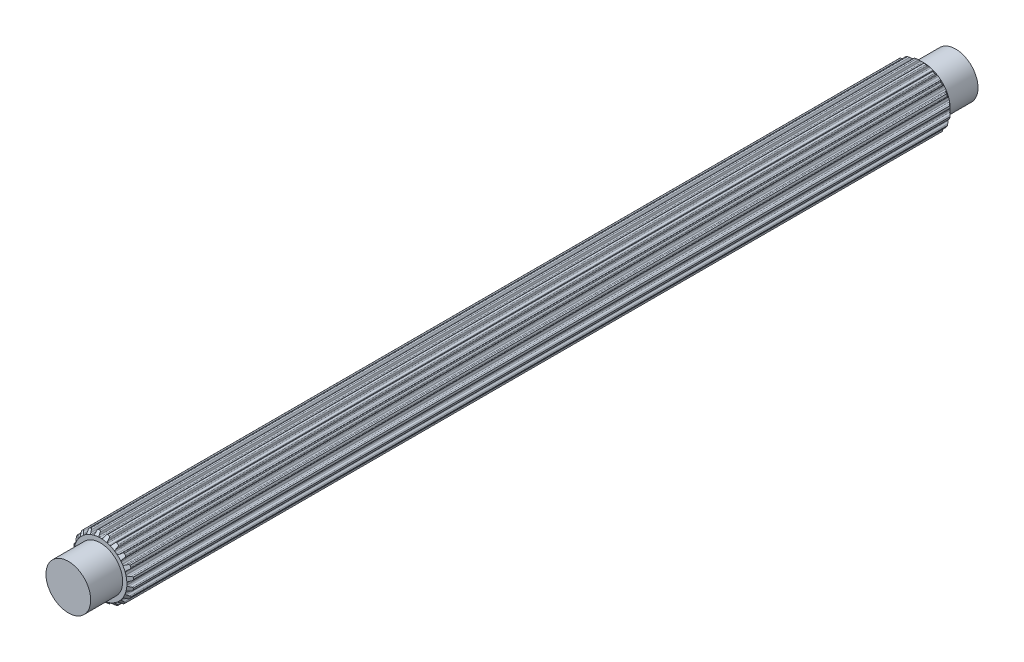
SolidWorks part; units mm, degrees
ref_plane "Front Plane" through (0, 0, 0) normal (0, 0, 1) x (1, 0, 0)
ref_plane "Top Plane" through (0, 0, 0) normal (0, 1, 0) x (1, 0, 0)
ref_plane "Right Plane" through (0, 0, 0) normal (1, 0, 0) x (0, 0, -1)
sketch "Sketch1" plane through (0, 0, 0) normal (0, 0, 1) x (1, 0, 0)
  line L0 (-0.1069, 2.9699) -> (0.1069, 2.9699)
  line L1 (0.3159, 3.2375) -> (0.2537, 3.0575)
  line L2 (-0.2964, 3.2367) -> (-0.2318, 3.0575)
  line L3 (-0.2964, 3.2367) -> (0.3159, 3.2375) construction
  line L4 (0, 3.3252) -> (0, 0) construction
  line L5 (-0.2318, 3.0575) -> (0.2537, 3.0575) construction
  line L6 (-0.4281, 3.3241) -> (0.4281, 3.3263) construction
  line L7 (0.7183, 3.1698) -> (0.7244, 2.9795)
  line L8 (0.816, 2.8576) -> (1.0195, 2.7915)
  line L9 (1.3009, 2.9815) -> (1.1862, 2.8295)
  line L10 (1.6627, 2.7927) -> (1.6097, 2.6099)
  line L11 (1.6591, 2.4655) -> (1.8322, 2.3398)
  line L12 (2.1585, 2.4335) -> (2.0025, 2.3245)
  line L13 (2.4443, 2.1423) -> (2.3374, 1.9847)
  line L14 (2.3398, 1.8322) -> (2.4655, 1.6591)
  line L15 (2.8049, 1.6474) -> (2.6228, 1.5919)
  line L16 (2.9866, 1.2821) -> (2.8363, 1.1653)
  line L17 (2.7915, 1.0195) -> (2.8576, 0.816)
  line L18 (3.1767, 0.7) -> (2.9863, 0.7035)
  line L19 (3.2367, 0.2964) -> (3.0575, 0.2318)
  line L20 (2.9699, 0.1069) -> (2.9699, -0.1069)
  line L21 (3.2375, -0.3159) -> (3.0575, -0.2537)
  line L22 (3.1698, -0.7183) -> (2.9795, -0.7244)
  line L23 (2.8576, -0.816) -> (2.7915, -1.0195)
  line L24 (2.9815, -1.3009) -> (2.8295, -1.1862)
  line L25 (2.7927, -1.6627) -> (2.6099, -1.6097)
  line L26 (2.4655, -1.6591) -> (2.3398, -1.8322)
  line L27 (2.4335, -2.1585) -> (2.3245, -2.0025)
  line L28 (2.1423, -2.4443) -> (1.9847, -2.3374)
  line L29 (1.8322, -2.3398) -> (1.6591, -2.4655)
  line L30 (1.6474, -2.8049) -> (1.5919, -2.6228)
  line L31 (1.2821, -2.9866) -> (1.1653, -2.8363)
  line L32 (1.0195, -2.7915) -> (0.816, -2.8576)
  line L33 (0.7, -3.1767) -> (0.7035, -2.9863)
  line L34 (0.2964, -3.2367) -> (0.2318, -3.0575)
  line L35 (0.1069, -2.9699) -> (-0.1069, -2.9699)
  line L36 (-0.3159, -3.2375) -> (-0.2537, -3.0575)
  line L37 (-0.7183, -3.1698) -> (-0.7244, -2.9795)
  line L38 (-0.816, -2.8576) -> (-1.0195, -2.7915)
  line L39 (-1.3009, -2.9815) -> (-1.1862, -2.8295)
  line L40 (-1.6627, -2.7927) -> (-1.6097, -2.6099)
  line L41 (-1.6591, -2.4655) -> (-1.8322, -2.3398)
  line L42 (-2.1585, -2.4335) -> (-2.0025, -2.3245)
  line L43 (-2.4443, -2.1423) -> (-2.3374, -1.9847)
  line L44 (-2.3398, -1.8322) -> (-2.4655, -1.6591)
  line L45 (-2.8049, -1.6474) -> (-2.6228, -1.5919)
  line L46 (-2.9866, -1.2821) -> (-2.8363, -1.1653)
  line L47 (-2.7915, -1.0195) -> (-2.8576, -0.816)
  line L48 (-3.1767, -0.7) -> (-2.9863, -0.7035)
  line L49 (-3.2367, -0.2964) -> (-3.0575, -0.2318)
  line L50 (-2.9699, -0.1069) -> (-2.9699, 0.1069)
  line L51 (-3.2375, 0.3159) -> (-3.0575, 0.2537)
  line L52 (-3.1698, 0.7183) -> (-2.9795, 0.7244)
  line L53 (-2.8576, 0.816) -> (-2.7915, 1.0195)
  line L54 (-2.9815, 1.3009) -> (-2.8295, 1.1862)
  line L55 (-2.7927, 1.6627) -> (-2.6099, 1.6097)
  line L56 (-2.4655, 1.6591) -> (-2.3398, 1.8322)
  line L57 (-2.4335, 2.1585) -> (-2.3245, 2.0025)
  line L58 (-2.1423, 2.4443) -> (-1.9847, 2.3374)
  line L59 (-1.8322, 2.3398) -> (-1.6591, 2.4655)
  line L60 (-1.6474, 2.8049) -> (-1.5919, 2.6228)
  line L61 (-1.2821, 2.9866) -> (-1.1653, 2.8363)
  line L62 (-1.0195, 2.7915) -> (-0.816, 2.8576)
  line L63 (-0.7, 3.1767) -> (-0.7035, 2.9863)
  line L64 (0.4281, 3.3263) -> (0.62, 3.2938)
  line L65 (1.4351, 3.0312) -> (1.6075, 2.9409)
  line L66 (2.3015, 2.4394) -> (2.4376, 2.3003)
  line L67 (2.9427, 1.6088) -> (3.0291, 1.4344)
  line L68 (3.2958, 0.6207) -> (3.3241, 0.4281)
  line L69 (3.3263, -0.4281) -> (3.2938, -0.62)
  line L70 (3.0312, -1.4351) -> (2.9409, -1.6075)
  line L71 (2.4394, -2.3015) -> (2.3003, -2.4376)
  line L72 (1.6088, -2.9427) -> (1.4344, -3.0291)
  line L73 (0.6207, -3.2958) -> (0.4281, -3.3241)
  line L74 (-0.4281, -3.3263) -> (-0.62, -3.2938)
  line L75 (-1.4351, -3.0312) -> (-1.6075, -2.9409)
  line L76 (-2.3015, -2.4394) -> (-2.4376, -2.3003)
  line L77 (-2.9427, -1.6088) -> (-3.0291, -1.4344)
  line L78 (-3.2958, -0.6207) -> (-3.3241, -0.4281)
  line L79 (-3.3263, 0.4281) -> (-3.2938, 0.62)
  line L80 (-3.0312, 1.4351) -> (-2.9409, 1.6075)
  line L81 (-2.4394, 2.3015) -> (-2.3003, 2.4376)
  line L82 (-1.6088, 2.9427) -> (-1.4344, 3.0291)
  line L83 (-0.6207, 3.2958) -> (-0.4281, 3.3241)
  arc A0 (0.2537, 3.0575) -> (0.1069, 2.9699) centre (0.1283, 3.1009) cw
  arc A1 (-0.2318, 3.0575) -> (-0.1069, 2.9699) centre (-0.1069, 3.1026) ccw
  arc A2 (0.62, 3.2938) -> (0.7183, 3.1698) centre (0.5856, 3.1656) cw
  arc A3 (0.7244, 2.9795) -> (0.816, 2.8576) centre (0.857, 2.9838) ccw
  arc A4 (-0.4281, 3.3241) -> (-0.2964, 3.2367) centre (-0.4213, 3.1916) cw
  arc A5 (0.4281, 3.3263) -> (0.3159, 3.2375) centre (0.4413, 3.1942) ccw
  arc A6 (1.1862, 2.8295) -> (1.0195, 2.7915) centre (1.0802, 2.9095) cw
  arc A7 (1.4351, 3.0312) -> (1.3009, 2.9815) centre (1.4068, 2.9015) ccw
  arc A8 (1.6075, 2.9409) -> (1.6627, 2.7927) centre (1.5352, 2.8297) cw
  arc A9 (1.6097, 2.6099) -> (1.6591, 2.4655) centre (1.7371, 2.5729) ccw
  arc A10 (2.0025, 2.3245) -> (1.8322, 2.3398) centre (1.9264, 2.4332) cw
  arc A11 (2.3015, 2.4394) -> (2.1585, 2.4335) centre (2.2346, 2.3248) ccw
  arc A12 (2.4376, 2.3003) -> (2.4443, 2.1423) centre (2.3345, 2.2168) cw
  arc A13 (2.3374, 1.9847) -> (2.3398, 1.8322) centre (2.4472, 1.9102) ccw
  arc A14 (2.6228, 1.5919) -> (2.4655, 1.6591) centre (2.5841, 1.7189) cw
  arc A15 (2.9427, 1.6088) -> (2.8049, 1.6474) centre (2.8436, 1.5205) ccw
  arc A16 (3.0291, 1.4344) -> (2.9866, 1.2821) centre (2.9052, 1.3869) cw
  arc A17 (2.8363, 1.1653) -> (2.7915, 1.0195) centre (2.9177, 1.0605) ccw
  arc A18 (2.9863, 0.7035) -> (2.8576, 0.816) centre (2.9887, 0.8362) cw
  arc A19 (3.2958, 0.6207) -> (3.1767, 0.7) centre (3.1743, 0.5673) ccw
  arc A20 (3.3241, 0.4281) -> (3.2367, 0.2964) centre (3.1916, 0.4213) cw
  arc A21 (3.0575, 0.2318) -> (2.9699, 0.1069) centre (3.1026, 0.1069) ccw
  arc A22 (3.0575, -0.2537) -> (2.9699, -0.1069) centre (3.1009, -0.1283) cw
  arc A23 (3.3263, -0.4281) -> (3.2375, -0.3159) centre (3.1942, -0.4413) ccw
  arc A24 (3.2938, -0.62) -> (3.1698, -0.7183) centre (3.1656, -0.5856) cw
  arc A25 (2.9795, -0.7244) -> (2.8576, -0.816) centre (2.9838, -0.857) ccw
  arc A26 (2.8295, -1.1862) -> (2.7915, -1.0195) centre (2.9095, -1.0802) cw
  arc A27 (3.0312, -1.4351) -> (2.9815, -1.3009) centre (2.9015, -1.4068) ccw
  arc A28 (2.9409, -1.6075) -> (2.7927, -1.6627) centre (2.8297, -1.5352) cw
  arc A29 (2.6099, -1.6097) -> (2.4655, -1.6591) centre (2.5729, -1.7371) ccw
  arc A30 (2.3245, -2.0025) -> (2.3398, -1.8322) centre (2.4332, -1.9264) cw
  arc A31 (2.4394, -2.3015) -> (2.4335, -2.1585) centre (2.3248, -2.2346) ccw
  arc A32 (2.3003, -2.4376) -> (2.1423, -2.4443) centre (2.2168, -2.3345) cw
  arc A33 (1.9847, -2.3374) -> (1.8322, -2.3398) centre (1.9102, -2.4472) ccw
  arc A34 (1.5919, -2.6228) -> (1.6591, -2.4655) centre (1.7189, -2.5841) cw
  arc A35 (1.6088, -2.9427) -> (1.6474, -2.8049) centre (1.5205, -2.8436) ccw
  arc A36 (1.4344, -3.0291) -> (1.2821, -2.9866) centre (1.3869, -2.9052) cw
  arc A37 (1.1653, -2.8363) -> (1.0195, -2.7915) centre (1.0605, -2.9177) ccw
  arc A38 (0.7035, -2.9863) -> (0.816, -2.8576) centre (0.8362, -2.9887) cw
  arc A39 (0.6207, -3.2958) -> (0.7, -3.1767) centre (0.5673, -3.1743) ccw
  arc A40 (0.4281, -3.3241) -> (0.2964, -3.2367) centre (0.4213, -3.1916) cw
  arc A41 (0.2318, -3.0575) -> (0.1069, -2.9699) centre (0.1069, -3.1026) ccw
  arc A42 (-0.2537, -3.0575) -> (-0.1069, -2.9699) centre (-0.1283, -3.1009) cw
  arc A43 (-0.4281, -3.3263) -> (-0.3159, -3.2375) centre (-0.4413, -3.1942) ccw
  arc A44 (-0.62, -3.2938) -> (-0.7183, -3.1698) centre (-0.5856, -3.1656) cw
  arc A45 (-0.7244, -2.9795) -> (-0.816, -2.8576) centre (-0.857, -2.9838) ccw
  arc A46 (-1.1862, -2.8295) -> (-1.0195, -2.7915) centre (-1.0802, -2.9095) cw
  arc A47 (-1.4351, -3.0312) -> (-1.3009, -2.9815) centre (-1.4068, -2.9015) ccw
  arc A48 (-1.6075, -2.9409) -> (-1.6627, -2.7927) centre (-1.5352, -2.8297) cw
  arc A49 (-1.6097, -2.6099) -> (-1.6591, -2.4655) centre (-1.7371, -2.5729) ccw
  arc A50 (-2.0025, -2.3245) -> (-1.8322, -2.3398) centre (-1.9264, -2.4332) cw
  arc A51 (-2.3015, -2.4394) -> (-2.1585, -2.4335) centre (-2.2346, -2.3248) ccw
  arc A52 (-2.4376, -2.3003) -> (-2.4443, -2.1423) centre (-2.3345, -2.2168) cw
  arc A53 (-2.3374, -1.9847) -> (-2.3398, -1.8322) centre (-2.4472, -1.9102) ccw
  arc A54 (-2.6228, -1.5919) -> (-2.4655, -1.6591) centre (-2.5841, -1.7189) cw
  arc A55 (-2.9427, -1.6088) -> (-2.8049, -1.6474) centre (-2.8436, -1.5205) ccw
  arc A56 (-3.0291, -1.4344) -> (-2.9866, -1.2821) centre (-2.9052, -1.3869) cw
  arc A57 (-2.8363, -1.1653) -> (-2.7915, -1.0195) centre (-2.9177, -1.0605) ccw
  arc A58 (-2.9863, -0.7035) -> (-2.8576, -0.816) centre (-2.9887, -0.8362) cw
  arc A59 (-3.2958, -0.6207) -> (-3.1767, -0.7) centre (-3.1743, -0.5673) ccw
  arc A60 (-3.3241, -0.4281) -> (-3.2367, -0.2964) centre (-3.1916, -0.4213) cw
  arc A61 (-3.0575, -0.2318) -> (-2.9699, -0.1069) centre (-3.1026, -0.1069) ccw
  arc A62 (-3.0575, 0.2537) -> (-2.9699, 0.1069) centre (-3.1009, 0.1283) cw
  arc A63 (-3.3263, 0.4281) -> (-3.2375, 0.3159) centre (-3.1942, 0.4413) ccw
  arc A64 (-3.2938, 0.62) -> (-3.1698, 0.7183) centre (-3.1656, 0.5856) cw
  arc A65 (-2.9795, 0.7244) -> (-2.8576, 0.816) centre (-2.9838, 0.857) ccw
  arc A66 (-2.8295, 1.1862) -> (-2.7915, 1.0195) centre (-2.9095, 1.0802) cw
  arc A67 (-3.0312, 1.4351) -> (-2.9815, 1.3009) centre (-2.9015, 1.4068) ccw
  arc A68 (-2.9409, 1.6075) -> (-2.7927, 1.6627) centre (-2.8297, 1.5352) cw
  arc A69 (-2.6099, 1.6097) -> (-2.4655, 1.6591) centre (-2.5729, 1.7371) ccw
  arc A70 (-2.3245, 2.0025) -> (-2.3398, 1.8322) centre (-2.4332, 1.9264) cw
  arc A71 (-2.4394, 2.3015) -> (-2.4335, 2.1585) centre (-2.3248, 2.2346) ccw
  arc A72 (-2.3003, 2.4376) -> (-2.1423, 2.4443) centre (-2.2168, 2.3345) cw
  arc A73 (-1.9847, 2.3374) -> (-1.8322, 2.3398) centre (-1.9102, 2.4472) ccw
  arc A74 (-1.5919, 2.6228) -> (-1.6591, 2.4655) centre (-1.7189, 2.5841) cw
  arc A75 (-1.6088, 2.9427) -> (-1.6474, 2.8049) centre (-1.5205, 2.8436) ccw
  arc A76 (-1.4344, 3.0291) -> (-1.2821, 2.9866) centre (-1.3869, 2.9052) cw
  arc A77 (-1.1653, 2.8363) -> (-1.0195, 2.7915) centre (-1.0605, 2.9177) ccw
  arc A78 (-0.7035, 2.9863) -> (-0.816, 2.8576) centre (-0.8362, 2.9887) cw
  arc A79 (-0.6207, 3.2958) -> (-0.7, 3.1767) centre (-0.5673, 3.1743) ccw
  point P14 (0, 2.9699)
  point P247 (0, 0)
  dimension "D4" = 0.1327
  dimension "D8" = 20
  dimension "D1" = 2.9699
  dimension "D2" = 0.2139
  dimension "D3" = 0.1904
  dimension "D5" = 0.0877
  dimension "D6" = 0.4855
  dimension "D7" = 0.8563
extrude "Boss-Extrude1" add sketch "Sketch1" along normal mid plane 92.0953
sketch "Sketch2" plane through (0, 0, 0) normal (0, 0, 1) x (1, 0, 0)
  circle A0 centre (0, 0) radius 2.5019
  dimension "D1" = 5.0038
extrude "Boss-Extrude2" add sketch "Sketch2" along normal mid plane 99.2581
sketch "Sketch4" plane through (0, 0, 49.6291) normal (0, 0, 1) x (1, 0, 0)
  circle A0 centre (0, 0) radius 2.5019 construction
  point P0 (0, 0)
sketch "Sketch5" plane through (0, 0, -49.6291) normal (0, 0, -1) x (-1, 0, 0)
  circle A0 centre (0, 0) radius 2.5019 construction
  point P0 (0, 0)
sketch "Sketch3" plane through (0, 0, 0) normal (1, 0, 0) x (0, 0, -1)
  line L0 (-44.9164, 4.1011) -> (-46.0477, 2.9699)
  line L1 (-46.0477, 2.9699) -> (-46.0477, 4.1011)
  line L2 (-46.0477, 4.1011) -> (-44.9164, 4.1011)
  line L3 (-46.0477, 2.5019) -> (-46.0477, -2.5019) construction
  line L5 (-14.3608, 0) -> (13.2171, 0) construction
  line L7 (46.0477, 42.7615) -> (46.0477, 2.9699)
  line L8 (46.0477, 2.9699) -> (26.1518, 22.8657)
  line L9 (26.1518, 22.8657) -> (46.0477, 42.7615)
  line L10 (46.0477, -2.5019) -> (46.0477, 2.5019) construction
  point P6 (-4.866, 6.1438)
  dimension "D1" = 45
  dimension "D2" = 45
revolve "Cut-Revolve1" cut sketch "Sketch3" angle 360 about L5
